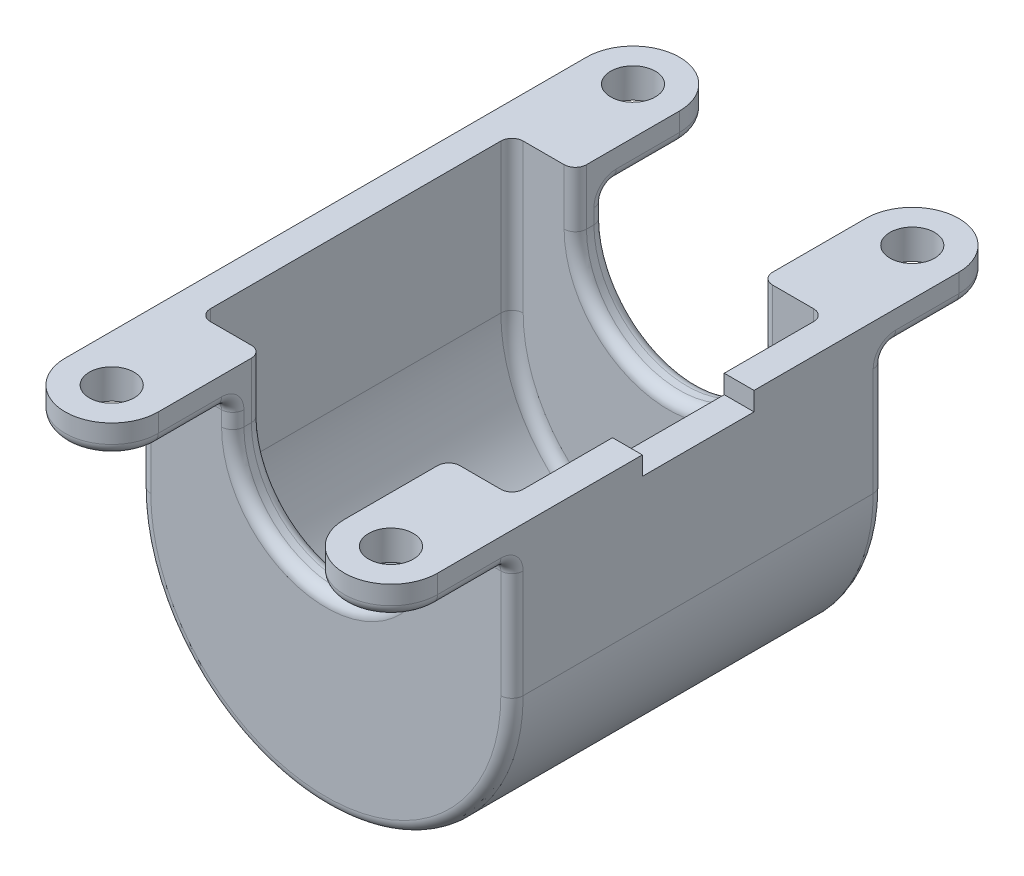
SolidWorks part; units mm, degrees
ref_plane "Front Plane" through (0, 0, 0) normal (0, 0, 1) x (1, 0, 0)
ref_plane "Top Plane" through (0, 0, 0) normal (0, 1, 0) x (1, 0, 0)
ref_plane "Right Plane" through (0, 0, 0) normal (1, 0, 0) x (0, 0, -1)
sketch "Sketch1" plane through (0, 0, 0) normal (0, 0, 1) x (1, 0, 0)
  line L0 (-25, 15) -> (-25, 0)
  line L1 (25, 0) -> (25, 15)
  line L2 (25, 15) -> (50, 15)
  line L3 (50, 15) -> (50, -25)
  line L4 (-25, 15) -> (-50, 15)
  line L5 (-50, 15) -> (-50, -25)
  arc A0 (-25, 0) -> (25, 0) centre (0, 0) ccw
  arc A1 (-50, -25) -> (50, -25) centre (0, -25) ccw
  dimension "D1" = 25
  dimension "D2" = 50
  dimension "D3" = 90
  dimension "D4" = 40
extrude "Boss-Extrude1" add sketch "Sketch1" along normal mid plane 100
shell "Shell1" thickness 8
sketch "Sketch2" plane through (0, 15, 0) normal (0, 1, 0) x (1, 0, 0)
  line L0 (-50, -50) -> (-50, 50) construction
  line L1 (-50, -50) -> (-25, -50)
  line L2 (-50, -50) -> (-50, -70)
  line L3 (-50, -70) -> (-25, -70) construction
  line L4 (-25, -50) -> (-25, -70)
  line L5 (-50, 0) -> (50, 0) construction
  line L6 (50, -50) -> (50, 50) construction
  arc A0 (-50, -70) -> (-25, -70) centre (-37.5, -70) ccw
  dimension "D1" = 70
extrude "Boss-Extrude2" add sketch "Sketch2" against normal blind 8
hole_wizard "Ø12.0 (12) Diameter Hole1" positions "Sketch4" profile "Sketch3" hole size "Ø12.0" standard "ANSI Metric" end condition through all
sketch "Sketch4" plane through (0, 15, 0) normal (0, 1, 0) x (1, 0, 0)
  point P0 (-37.5, -70)
sketch "Sketch3" plane through (-37.5, 15, 70) normal (1, 0, 0) x (0, 0, 1)
  line L0 (0, 0) -> (0, 90)
  line L1 (0, 90) -> (6, 90)
  line L2 (6, 90) -> (6, 0)
  line L5 (6, 0) -> (0, 0)
  line L11 (0, -6.35) -> (0, 107.95) construction
  dimension "Thru Hole Dia." = 12
  dimension "Thru Hole Depth" = 90
mirror "Mirror1" about plane through (0, 0, 0) normal (1, 0, 0) of "Ø12.0 (12) Diameter Hole1", "Boss-Extrude2"
mirror "Mirror2" about plane through (0, 0, 0) normal (0, 0, 1) of "Mirror1", "Boss-Extrude2", "Ø12.0 (12) Diameter Hole1"
sketch "Sketch6" plane through (0, 0, 0) normal (1, 0, 0) x (0, 0, -1)
  line L0 (-70, 15) -> (70, 15) construction
  line L1 (-15, 20) -> (15, 20)
  line L2 (-15, 20) -> (-15, 10)
  line L3 (-15, 10) -> (15, 10)
  line L4 (15, 20) -> (15, 10)
  line L5 (-15, 20) -> (15, 10) construction
  line L6 (-15, 10) -> (15, 20) construction
  point P0 (0, 15)
  dimension "D1" = 5
  dimension "D2" = 30
extrude "Cut-Extrude1" cut sketch "Sketch6" along normal through all
fillet "Fillet1" radius 3 4 edges at (-37.5, 7, -50) (37.5, 7, 50)
fillet "Fillet2" radius 3 44 edges at (0, -75, 50) (-37.5, 7, -82.5) (-25, 7, -61.5) (50, -10.5, 50) (-50, 7, -61.5) (-50, -10.5, -50) (50, 7, 61.5) (25, 2, 50) (-50, 6.1213, -50.8787) (-25, 6.1213, -50.8787) (50, 6.1213, -50.8787) (25, 6.1213, -50.8787) (50, 6.1213, 50.8787) (25, 6.1213, 50.8787) (-50, 6.1213, 50.8787) (-25, 6.1213, 50.8787) (0, -25, 50) (-42, -5, -42) (0, -67, -42) (42, -5, -42) (25, 7.5, -42) (0, -25, -42) (-25, 7.5, -42) (-42, -5, 42) (0, -67, 42) (42, -5, 42) (25, 7.5, 42) (0, -25, 42) (-25, 7.5, 42) (-37.5, 7, 82.5) (37.5, 7, 82.5) (25, 7, 61.5) (-25, 2, -50) (0, -25, -50) (37.5, 7, -82.5) (0, -75, -50)
